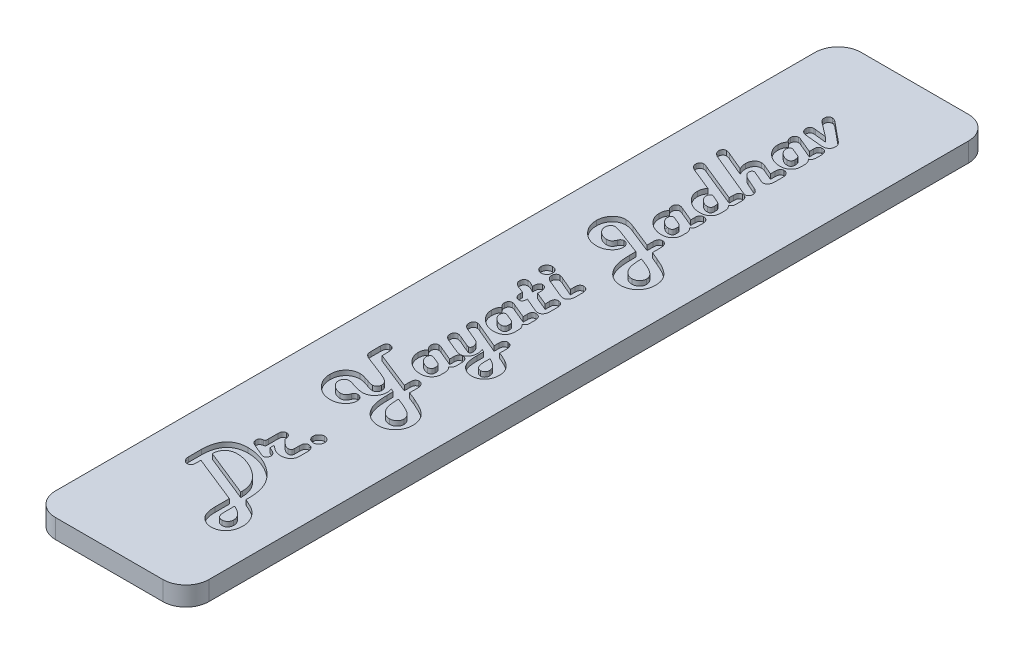
SolidWorks part; units mm, degrees
ref_plane "Front Plane" through (0, 0, 0) normal (0, 0, 1) x (1, 0, 0)
ref_plane "Top Plane" through (0, 0, 0) normal (0, 1, 0) x (1, 0, 0)
ref_plane "Right Plane" through (0, 0, 0) normal (1, 0, 0) x (0, 0, -1)
sketch "Sketch1" plane through (0, 0, 0) normal (0, 0, 1) x (1, 0, 0)
  line L0 (0, 1.5875) -> (0, -1.5875)
  line L1 (-12.7, 0) -> (12.7, 0) construction
  point P6 (0, 0)
  dimension "Width" = 25.4
  dimension "Thk" = 3.175
sketch "Sketch2" plane through (0, 0, 0) normal (1, 0, 0) x (0, 0, -1)
  line L0 (66.675, 0) -> (-66.675, 0)
  point P4 (0, 0)
  dimension "Length" = 133.35
sketch "Sketch3" plane through (0, 0, 0) normal (0, 0, 1) x (1, 0, 0)
  line L1 (12.7, 1.5875) -> (-12.7, 1.5875)
  line L2 (12.7, 1.5875) -> (12.7, -1.5875)
  line L3 (12.7, -1.5875) -> (-12.7, -1.5875)
  line L4 (-12.7, 1.5875) -> (-12.7, -1.5875)
  line L5 (12.7, 1.5875) -> (-12.7, -1.5875) construction
  line L6 (12.7, -1.5875) -> (-12.7, 1.5875) construction
  point P0 (0, 0)
extrude "Boss-Extrude1" add sketch "Sketch3" along normal up to vertex (66.675 mm away) and the other way up to vertex (66.675 mm away) up to point (0, 0, 66.675) other way up to point (0, 0, -66.675)
sketch "Sketch5" plane through (0, 1.5875, 0) normal (0, 1, 0) x (1, 0, 0)
  line L2 (9.652, -66.675) -> (-9.398, -66.675) construction
  line L3 (-12.7, -63.5025) -> (-12.7, 63.627) construction
  line L12 (12.7, -66.675) -> (12.7, 66.675)
  line L13 (12.7, 66.675) -> (-12.7, 66.675)
  line L14 (-12.7, 66.675) -> (-12.7, -66.675)
  line L15 (-12.7, -66.675) -> (12.7, -66.675)
  line L16 (12.7, -62.865) -> (12.7, 62.865)
  line L17 (8.89, 66.675) -> (-8.89, 66.675)
  line L18 (-12.7, 62.865) -> (-12.7, -62.865)
  line L19 (-8.89, -66.675) -> (8.89, -66.675)
  arc A8 (12.7, 62.865) -> (8.89, 66.675) centre (8.89, 62.865) ccw
  arc A9 (-8.89, 66.675) -> (-12.7, 62.865) centre (-8.89, 62.865) ccw
  arc A10 (12.7, -62.865) -> (8.89, -66.675) centre (8.89, -62.865) cw
  arc A11 (-8.89, -66.675) -> (-12.7, -62.865) centre (-8.89, -62.865) cw
  dimension "D2" = 3.81
  dimension "D1" = 0
extrude "Cut-Extrude2" cut sketch "Sketch5" against normal through all flip side to cut
sketch "Sketch4" plane through (0, 1.5875, 0) normal (0, 1, 0) x (1, 0, 0)
  line L0 (0, 0) -> (2.54, 0) construction
  line L1 (2.54, -66.675) -> (2.54, 66.675) construction
  line L2 (8.89, 66.675) -> (-8.89, 66.675) construction
  text T0 "Dr. Yayati Jadhav" font "Harlow Solid Italic" height in points 36
  point P8 (2.54, 0)
  dimension "D1" = 2.54
extrude "Cut-Extrude1" cut sketch "Sketch4" against normal blind 0.7937
